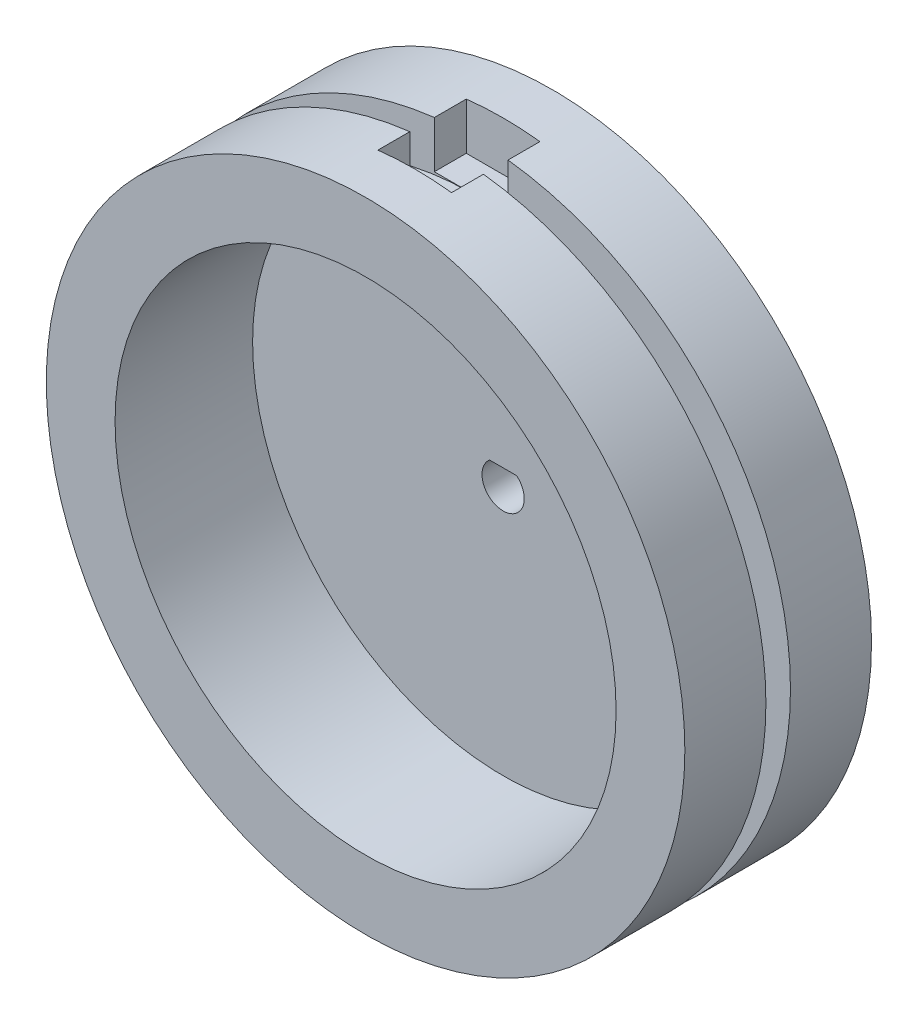
SolidWorks part; units mm, degrees
ref_plane "Front Plane" through (0, 0, 0) normal (0, 0, 1) x (1, 0, 0)
ref_plane "Top Plane" through (0, 0, 0) normal (0, 1, 0) x (1, 0, 0)
ref_plane "Right Plane" through (0, 0, 0) normal (1, 0, 0) x (0, 0, -1)
sketch "Sketch2" plane through (0, 0, 0) normal (1, 0, 0) x (0, 0, -1)
  line L0 (0, 0) -> (0, 32.5)
  line L1 (0, 32.5) -> (-8.25, 32.5)
  line L2 (-19, 32.5) -> (-19, 25.5)
  line L3 (-19, 25.5) -> (-5, 25.5)
  line L4 (-5, 25.5) -> (-5, 0)
  line L5 (-5, 0) -> (0, 0)
  line L6 (-8.25, 32.5) -> (-8.25, 27.5)
  line L7 (-8.25, 27.5) -> (-10.75, 27.5)
  line L8 (-10.75, 27.5) -> (-10.75, 32.5)
  line L9 (-10.75, 32.5) -> (-19, 32.5)
  dimension "D1" = 19
  dimension "D2" = 32.5
  dimension "D3" = 7
  dimension "D4" = 5
  dimension "D5" = 2.5
  dimension "D6" = 8.25
  dimension "D7" = 5
revolve "Revolve1" add sketch "Sketch2" angle 360 about L5
ref_plane "Plane1" through (0, 32.5, 0) normal (0, 1, 0) x (1, 0, 0)
sketch "Sketch7" plane through (0, 32.5, 0) normal (0, 1, 0) x (1, 0, 0)
  line L1 (-3.75, -14) -> (3.75, -14)
  line L2 (-3.75, -14) -> (-3.75, -5)
  line L3 (-3.75, -5) -> (3.75, -5)
  line L4 (3.75, -14) -> (3.75, -5)
  line L5 (-3.75, -9.5) -> (3.75, -9.5) construction
  line L6 (32.5, 0) -> (-32.5, 0) construction
  line L7 (0, -5) -> (0, 0) construction
  dimension "D1" = 9.5
  dimension "D2" = 9
  dimension "D3" = 7.5
extrude "Cut-Extrude1" cut sketch "Sketch7" against normal blind 5
mirror "Mirror1" about plane through (0, 0, 0) normal (0, 1, 0) of "Cut-Extrude1"
sketch "Sketch8" plane through (0, 0, 0) normal (0, 0, -1) x (-1, 0, 0)
  line L0 (-1.3784, 1.65) -> (1.3784, 1.65)
  arc A0 (-1.3784, 1.65) -> (1.3784, 1.65) centre (0, 0) ccw
  dimension "D1" = 4.3
  dimension "D2" = 1.65
extrude "Shaft Hole" cut sketch "Sketch8" against normal through all
